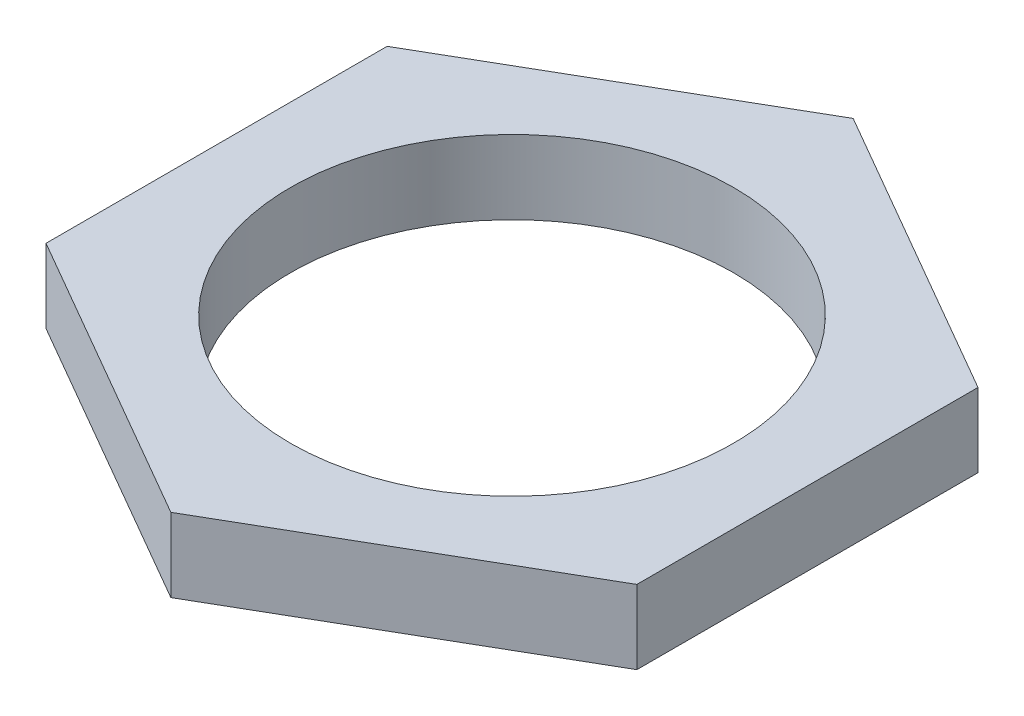
SolidWorks part; units mm, degrees
ref_plane "Front Plane" through (0, 0, 0) normal (0, 0, 1) x (1, 0, 0)
ref_plane "Top Plane" through (0, 0, 0) normal (0, 1, 0) x (1, 0, 0)
ref_plane "Right Plane" through (0, 0, 0) normal (1, 0, 0) x (0, 0, -1)
sketch "Sketch2" plane through (0, 0, 0) normal (0, 1, 0) x (1, 0, 0)
  line L1 (0, 4.6188) -> (-4, 2.3094)
  line L2 (-4, 2.3094) -> (-4, -2.3094)
  line L3 (-4, -2.3094) -> (0, -4.6188)
  line L4 (0, -4.6188) -> (4, -2.3094)
  line L5 (4, -2.3094) -> (4, 2.3094)
  line L6 (4, 2.3094) -> (0, 4.6188)
  circle A0 centre (0, 0) radius 4 construction
  dimension "D1" = 8
extrude "Boss-Extrude2" add sketch "Sketch2" along normal blind 1
sketch "Sketch4" plane through (0, 1, 0) normal (0, 1, 0) x (1, 0, 0)
  circle A0 centre (0, 0) radius 3
  dimension "D1" = 6
extrude "Cut-Extrude2" cut sketch "Sketch4" against normal up to next
